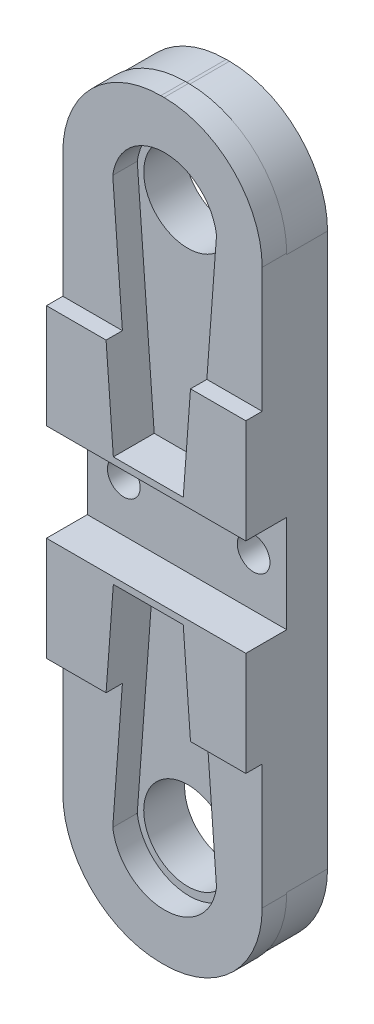
SolidWorks part; units mm, degrees
ref_plane "Front Plane" through (0, 0, 0) normal (0, 0, 1) x (1, 0, 0)
ref_plane "Top Plane" through (0, 0, 0) normal (0, 1, 0) x (1, 0, 0)
ref_plane "Right Plane" through (0, 0, 0) normal (1, 0, 0) x (0, 0, -1)
other "Graphic1"
ref_plane "Plane1" through (0, 0, 10) normal (0, 0, 1) x (1, 0, 0)
sketch "Sketch1" plane through (0, 0, 10) normal (0, 0, 1) x (1, 0, 0)
  line L1 (-188.2312, 182.8882) -> (-176.0312, 182.8882)
  line L2 (-188.2312, 182.8882) -> (-188.2312, 137.0882)
  line L3 (-188.2312, 137.0882) -> (-176.0312, 137.0882)
  line L4 (-176.0312, 182.8882) -> (-176.0312, 137.0882)
  dimension "D1" = 12.2
  dimension "D2" = 45.8
extrude "Boss-Extrude1" add sketch "Sketch1" along normal blind 2.5
fillet "Fillet1" radius 6 4 edges at (-176.0312, 182.8882, 11.25) (-188.2312, 182.8882, 11.25) (-176.0312, 137.0882, 11.25) (-188.2312, 137.0882, 11.25)
sketch "Sketch2" plane through (0, 0, 12.5) normal (0, 0, 1) x (1, 0, 0)
  line L0 (-188.2312, 159.9882) -> (-146.0551, 159.9882) construction
  line L2 (-176.0312, 143.0882) -> (-176.0312, 176.8882) construction
  line L3 (-176.0312, 162.9655) -> (-188.2312, 162.9655)
  line L4 (-176.0312, 162.9655) -> (-176.0312, 182.9655)
  line L5 (-176.0312, 182.9655) -> (-188.2312, 182.9655)
  line L6 (-188.2312, 162.9655) -> (-188.2312, 182.9655)
  line L7 (-188.2312, 176.8882) -> (-188.2312, 143.0882) construction
  line L8 (-176.0312, 137.0109) -> (-188.2312, 137.0109)
  line L9 (-188.2312, 157.0109) -> (-188.2312, 137.0109)
  line L10 (-176.0312, 157.0109) -> (-188.2312, 157.0109)
  line L11 (-176.0312, 157.0109) -> (-176.0312, 137.0109)
  dimension "D1" = 20
  dimension "D2" = 12.2
extrude "Boss-Extrude2" add sketch "Sketch2" along normal blind 2.5
fillet "Fillet2" radius 6 4 edges at (-188.2312, 182.9655, 13.75) (-176.0312, 182.9655, 13.75) (-188.2312, 137.0109, 13.75) (-176.0312, 137.0109, 13.75)
sketch "Sketch3" plane through (0, 0, 12.5) normal (0, 0, 1) x (1, 0, 0)
  circle A0 centre (-185.9997, 160.0579) radius 1
  circle A1 centre (-178.0549, 160.0579) radius 1
extrude "Cut-Extrude1" cut sketch "Sketch3" against normal blind 2.5
sketch "Sketch4" plane through (0, 0, 15) normal (0, 0, 1) x (1, 0, 0)
  line L0 (-184.1384, 163.3657) -> (-179.8616, 163.3657)
  line L1 (-179.8616, 163.3657) -> (-178.8249, 177.2648)
  line L2 (-184.1384, 163.3657) -> (-185.1751, 177.2648)
  line L3 (-176.0312, 159.9882) -> (-170.1506, 159.9882) construction
  line L4 (-176.0312, 157.0109) -> (-176.0312, 162.9655) construction
  line L5 (-184.1384, 156.6106) -> (-185.1751, 142.7116)
  line L6 (-184.1384, 156.6106) -> (-179.8616, 156.6106)
  line L7 (-179.8616, 156.6106) -> (-178.8249, 142.7116)
  arc A0 (-185.1751, 177.2648) -> (-178.8249, 177.2648) centre (-182, 176.8585) cw
  arc A1 (-185.1751, 142.7116) -> (-178.8249, 142.7116) centre (-182, 143.1178) ccw
extrude "Cut-Extrude2" cut sketch "Sketch4" against normal up to vertex (2.5 mm away)
sketch "Sketch5" plane through (0, 0, 12.5) normal (0, 0, 1) x (1, 0, 0)
  line L0 (-176.0312, 159.9882) -> (-170.9247, 159.9882) construction
  line L1 (-176.0312, 157.0109) -> (-176.0312, 162.9655) construction
  circle A0 centre (-182.0806, 176.9002) radius 2.7
  circle A1 centre (-182.0806, 143.0762) radius 2.7
extrude "Cut-Extrude3" cut sketch "Sketch5" against normal blind 2.5
sketch "Sketch6" plane through (0, 0, 15) normal (0, 0, 1) x (1, 0, 0)
  line L1 (-176.0312, 169.3347) -> (-189.6126, 169.3347)
  line L2 (-176.0312, 169.3347) -> (-176.0312, 183.9195)
  line L3 (-176.0312, 183.9195) -> (-189.6126, 183.9195)
  line L4 (-189.6126, 169.3347) -> (-189.6126, 183.9195)
  line L5 (-176.0312, 159.9882) -> (-168.0066, 159.9882) construction
  line L6 (-176.0312, 157.0109) -> (-176.0312, 162.9655) construction
  line L7 (-176.0312, 136.0568) -> (-189.6126, 136.0568)
  line L8 (-189.6126, 150.6417) -> (-189.6126, 136.0568)
  line L9 (-176.0312, 150.6417) -> (-189.6126, 150.6417)
  line L10 (-176.0312, 150.6417) -> (-176.0312, 136.0568)
extrude "Cut-Extrude4" cut sketch "Sketch6" against normal blind 1
